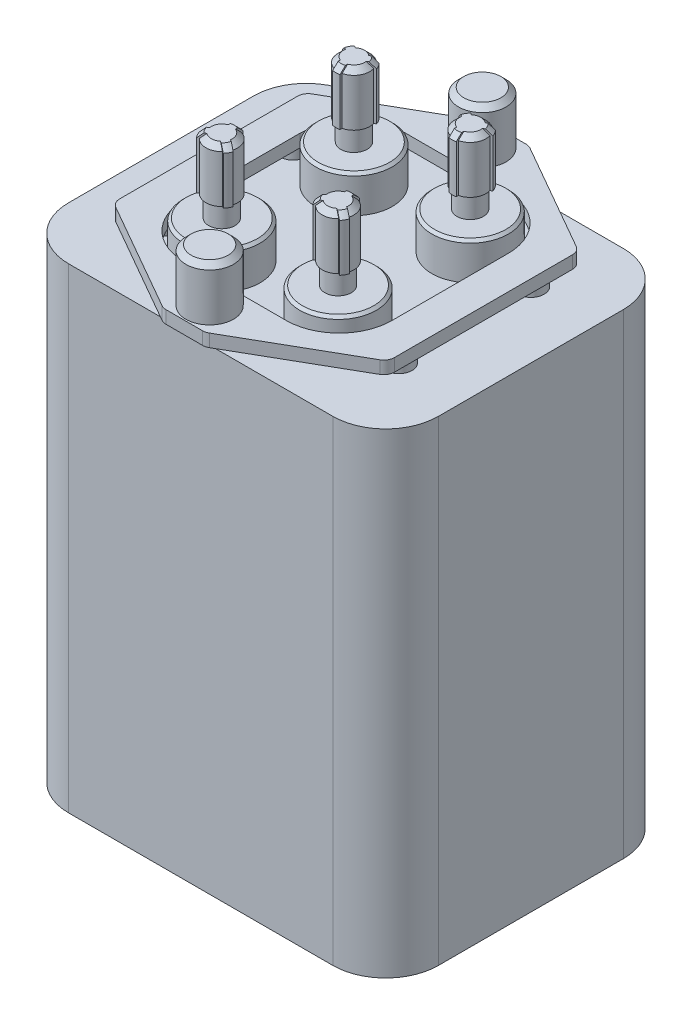
SolidWorks part; units mm, degrees
ref_plane "Front Plane" through (0, 0, 0) normal (0, 0, 1) x (1, 0, 0)
ref_plane "Top Plane" through (0, 0, 0) normal (0, 1, 0) x (1, 0, 0)
ref_plane "Right Plane" through (0, 0, 0) normal (1, 0, 0) x (0, 0, -1)
sketch "Sketch1" plane through (0, 0, 0) normal (0, 1, 0) x (1, 0, 0)
  line L1 (-31.75, -34.925) -> (31.75, -34.925)
  line L2 (-44.45, -22.225) -> (-44.45, 22.225)
  line L3 (-31.75, 34.925) -> (31.75, 34.925)
  line L4 (44.45, -22.225) -> (44.45, 22.225)
  line L5 (-44.45, -34.925) -> (44.45, 34.925) construction
  line L6 (-44.45, 34.925) -> (44.45, -34.925) construction
  arc A0 (44.45, 22.225) -> (31.75, 34.925) centre (31.75, 22.225) ccw
  arc A1 (-31.75, -34.925) -> (-44.45, -22.225) centre (-31.75, -22.225) cw
  arc A2 (31.75, -34.925) -> (44.45, -22.225) centre (31.75, -22.225) ccw
  arc A3 (-31.75, 34.925) -> (-44.45, 22.225) centre (-31.75, 22.225) ccw
  point P0 (0, 0)
  dimension "D3" = 12.7
  dimension "D1" = 88.9
  dimension "D2" = 69.85
extrude "Boss-Extrude1" add sketch "Sketch1" against normal blind 114.3
sketch "Sketch2" plane through (0, 0, 0) normal (0, 1, 0) x (1, 0, 0)
  line L0 (31.75, 34.925) -> (-31.75, 34.925) construction
  line L2 (-44.45, 22.225) -> (-44.45, -22.225) construction
  line L4 (0, 34.925) -> (0, -34.925) construction
  line L5 (-31.75, -34.925) -> (31.75, -34.925) construction
  line L6 (-44.45, 0) -> (44.45, 0) construction
  line L7 (44.45, -22.225) -> (44.45, 22.225) construction
  circle A0 centre (-28.575, 15.875) radius 3.175
  circle A2 centre (28.575, 15.875) radius 3.175
  circle A3 centre (28.575, -15.875) radius 3.175
  circle A4 centre (-28.575, -15.875) radius 3.175
  dimension "D3" = 6.35
  dimension "D1" = 19.05
  dimension "D2" = 15.875
extrude "Boss-Extrude2" add sketch "Sketch2" along normal blind 3.048
sketch "Sketch3" plane through (0, 3.048, 0) normal (0, 1, 0) x (1, 0, 0)
  line L0 (0, 26.67) -> (0, -26.67) construction
  line L1 (-33.02, -38.862) -> (33.02, -38.862)
  line L2 (-33.02, -38.862) -> (-33.02, 38.862)
  line L3 (-33.02, 38.862) -> (33.02, 38.862)
  line L4 (33.02, -38.862) -> (33.02, 38.862)
  line L5 (-33.02, -38.862) -> (33.02, 38.862) construction
  line L6 (-33.02, 38.862) -> (33.02, -38.862) construction
  line L7 (-12.319, 26.67) -> (12.319, 26.67)
  line L8 (-25.019, 13.97) -> (-25.019, -13.97)
  line L9 (-12.319, -26.67) -> (12.319, -26.67)
  line L10 (25.019, 13.97) -> (25.019, -13.97)
  line L11 (-25.019, 26.67) -> (25.019, -26.67) construction
  line L12 (-25.019, -26.67) -> (25.019, 26.67) construction
  line L13 (-25.019, 0) -> (25.019, 0) construction
  line L14 (33.02, 0) -> (-33.02, 0) construction
  line L15 (0, -38.862) -> (0, 38.862) construction
  line L16 (5.08, 38.862) -> (33.02, 22.86)
  line L17 (-5.08, 38.862) -> (-33.02, 22.86)
  line L18 (-33.02, -22.86) -> (-5.08, -38.862)
  line L19 (5.08, -38.862) -> (33.02, -22.86)
  arc A0 (12.319, -26.67) -> (25.019, -13.97) centre (12.319, -13.97) ccw
  arc A1 (-25.019, -13.97) -> (-12.319, -26.67) centre (-12.319, -13.97) ccw
  arc A2 (12.319, 26.67) -> (25.019, 13.97) centre (12.319, 13.97) cw
  arc A3 (-12.319, 26.67) -> (-25.019, 13.97) centre (-12.319, 13.97) ccw
  point P0 (0, 0)
  point P6 (0, 0)
  point P27 (-5.08, 26.67)
  point P28 (5.08, 26.67)
  point P29 (5.08, -26.67)
  point P30 (-5.08, -26.67)
  point P35 (5.08, -38.862)
  point P36 (-5.08, -38.862)
  point P37 (5.08, 38.862)
  point P38 (-5.08, 38.862)
  point P39 (-33.02, 22.86)
  point P40 (-33.02, -22.86)
  point P41 (33.02, -22.86)
  point P42 (33.02, 22.86)
  circle M1 centre (-28.575, 15.875) radius 3.175
  dimension "D5" = 12.7
  dimension "D1" = 66.04
  dimension "D2" = 77.724
  dimension "D3" = 50.038
  dimension "D4" = 53.34
  dimension "D6" = 5.08
  dimension "D7" = 22.86
  dimension "D8" = 10.16
extrude "Boss-Extrude3" add sketch "Sketch3" along normal blind 3.048 contours L1 L19 L4 L16 L3 L17 L2 L18 A3 L7 A2 L10 A0 L9 A1 L8 M1 | M1
sketch "Sketch4" plane through (0, 0, 0) normal (0, 1, 0) x (1, 0, 0)
  line L0 (-44.45, 0) -> (44.45, 0) construction
  line L1 (-44.45, 22.225) -> (-44.45, -22.225) construction
  line L2 (44.45, -22.225) -> (44.45, 22.225) construction
  line L3 (0, 35.4714) -> (0, -34.4228) construction
  line L5 (-31.75, -34.925) -> (31.75, -34.925) construction
  circle A0 centre (13.97, -15.875) radius 9.2075
  circle A1 centre (-13.97, -15.875) radius 9.2075
  circle A2 centre (13.97, 15.875) radius 9.2075
  circle A3 centre (-13.97, 15.875) radius 9.2075
  dimension "D1" = 18.415
  dimension "D2" = 30.48
  dimension "D3" = 19.05
extrude "Boss-Extrude4" add sketch "Sketch4" along normal blind 8.89
chamfer "Chamfer1" distance 0.635 angle 45 4 edges at (-13.97, 8.89, -6.6675) (-13.97, 8.89, 6.6675) (13.97, 8.89, -25.0825) (13.97, 8.89, 25.0825)
fillet "Fillet1" radius 2.54 8 edges at (33.02, 4.572, 22.86) (33.02, 4.572, -22.86) (5.08, 4.572, -38.862) (-5.08, 4.572, -38.862) (-33.02, 4.572, -22.86) (-33.02, 4.572, 22.86) (5.08, 4.572, 38.862) (-5.08, 4.572, 38.862)
sketch "Sketch5" plane through (0, 6.096, 0) normal (0, 1, 0) x (1, 0, 0)
  line L0 (0, 26.67) -> (0, 38.862) construction
  line L1 (0, 38.4529) -> (0, 38.862) construction
  line L2 (-4.4041, 38.862) -> (4.4041, 38.862) construction
  line L3 (-12.319, 26.67) -> (12.319, 26.67) construction
  line L4 (-33.02, 0) -> (33.02, 0) construction
  line L5 (-33.02, -21.3876) -> (-33.02, 21.3876) construction
  line L6 (33.02, -21.3876) -> (33.02, 21.3876) construction
  circle A0 centre (0, 32.766) radius 5.715
  circle A1 centre (0, -32.766) radius 5.715
  dimension "D1" = 11.43
extrude "Boss-Extrude5" add sketch "Sketch5" along normal blind 12.7
chamfer "Chamfer2" distance 1.27 angle 45 2 edges at (0, 18.796, -27.051) (0, 18.796, 27.051)
sketch "Sketch7" plane through (0, 8.89, 0) normal (0, 1, 0) x (1, 0, 0)
  line L0 (-44.4383, 0) -> (44.3129, 0) construction
  line L1 (0, -32.766) -> (0, 32.766) construction
  circle A0 centre (-13.97, -15.875) radius 3.175
  circle A1 centre (-13.97, 15.875) radius 3.175
  circle A2 centre (13.97, 15.875) radius 3.175
  circle A3 centre (13.97, -15.875) radius 3.175
  dimension "D1" = 6.35
extrude "Boss-Extrude6" add sketch "Sketch7" along normal blind 5.08
sketch "Sketch8" plane through (0, 13.97, 0) normal (0, 1, 0) x (1, 0, 0)
  line L0 (0, -32.766) -> (0, 32.766) construction
  line L1 (33.02, 0) -> (-33.02, 0) construction
  line L2 (33.02, -21.3876) -> (33.02, 21.3876) construction
  line L3 (-33.02, -21.3876) -> (-33.02, 21.3876) construction
  line L4 (-13.97, -11.565) -> (-13.97, -20.185) construction
  line L5 (-14.845, -11.6548) -> (-14.845, -12.1668)
  line L6 (-13.095, -11.6548) -> (-13.095, -12.1668)
  line L7 (-9.8777, -17.2274) -> (-10.3211, -16.9713)
  line L8 (-10.7527, -18.7429) -> (-11.1961, -18.4869)
  line L9 (-17.1873, -18.7429) -> (-16.7439, -18.4869)
  line L10 (-18.0623, -17.2274) -> (-17.6189, -16.9713)
  line L11 (13.97, -11.565) -> (13.97, -20.185) construction
  line L12 (18.0623, -17.2274) -> (17.6189, -16.9713)
  line L13 (17.1873, -18.7429) -> (16.7439, -18.4869)
  line L14 (10.7527, -18.7429) -> (11.1961, -18.4869)
  line L15 (9.8777, -17.2274) -> (10.3211, -16.9713)
  line L16 (13.095, -11.6548) -> (13.095, -12.1668)
  line L17 (14.845, -11.6548) -> (14.845, -12.1668)
  line L18 (13.97, 11.565) -> (13.97, 20.185) construction
  line L19 (-13.97, 11.565) -> (-13.97, 20.185) construction
  line L20 (14.845, 11.6548) -> (14.845, 12.1668)
  line L21 (13.095, 11.6548) -> (13.095, 12.1668)
  line L22 (9.8777, 17.2274) -> (10.3211, 16.9713)
  line L23 (10.7527, 18.7429) -> (11.1961, 18.4869)
  line L24 (17.1873, 18.7429) -> (16.7439, 18.4869)
  line L25 (18.0623, 17.2274) -> (17.6189, 16.9713)
  line L26 (-18.0623, 17.2274) -> (-17.6189, 16.9713)
  line L27 (-17.1873, 18.7429) -> (-16.7439, 18.4869)
  line L28 (-10.7527, 18.7429) -> (-11.1961, 18.4869)
  line L29 (-9.8777, 17.2274) -> (-10.3211, 16.9713)
  line L30 (-13.095, 11.6548) -> (-13.095, 12.1668)
  line L31 (-14.845, 11.6548) -> (-14.845, 12.1668)
  circle A0 centre (-13.97, -15.875) radius 3.81
  circle A1 centre (-13.97, -15.875) radius 4.31
  circle A2 centre (13.97, -15.875) radius 4.31
  circle A3 centre (13.97, -15.875) radius 3.81
  circle A4 centre (13.97, 15.875) radius 3.81
  circle A5 centre (13.97, 15.875) radius 4.31
  circle A6 centre (-13.97, 15.875) radius 4.31
  circle A7 centre (-13.97, 15.875) radius 3.81
  point P17 (-14.845, -11.6548)
  point P32 (-13.97, -15.875)
  circle M1 centre (-13.97, -15.875) radius 3.175
  dimension "D1" = 7.62
  dimension "D3" = 0.875
  dimension "D2" = 8.62
  dimension "D4" = 3
extrude "Boss-Extrude7" add sketch "Sketch8" along normal blind 12.7 contours A0 M1 | L10 A1 L9 A0 | L8 A1 L7 A0 | L6 A1 L5 A0 | M1 | L14 A3 L15 A2 | L12 A3 L13 A2 | A3 | L16 A3 L17 A2 | A4 | L25 A5 L24 A4 | L23 A5 L22 A4 | L21 A5 L20 A4 | A7 | L30 A7 L31 A6 | L28 A7 L29 A6 | L26 A7 L27 A6
chamfer "Chamfer3" distance 1.27 12 edges at (-17.2696, 26.67, 13.97) (-10.6704, 26.67, 13.97) (-13.97, 26.67, 19.685) (10.6704, 26.67, 13.97) (13.97, 26.67, 19.685) (17.2696, 26.67, 13.97) (10.6704, 26.67, -13.97) (13.97, 26.67, -19.685) (17.2696, 26.67, -13.97) (-17.2696, 26.67, -13.97) (-13.97, 26.67, -19.685) (-10.6704, 26.67, -13.97)
chamfer "Chamfer4" distance 1.27 12 edges at (17.7026, 26.67, 18.03) (13.97, 26.67, 11.565) (10.2374, 26.67, 18.03) (-13.97, 26.67, 11.565) (-10.2374, 26.67, 18.03) (-17.7026, 26.67, 18.03) (17.7026, 26.67, -18.03) (10.2374, 26.67, -18.03) (13.97, 26.67, -11.565) (-13.97, 26.67, -11.565) (-17.7026, 26.67, -18.03) (-10.2374, 26.67, -18.03)
equation "\"0.1inin\"=0.05"
